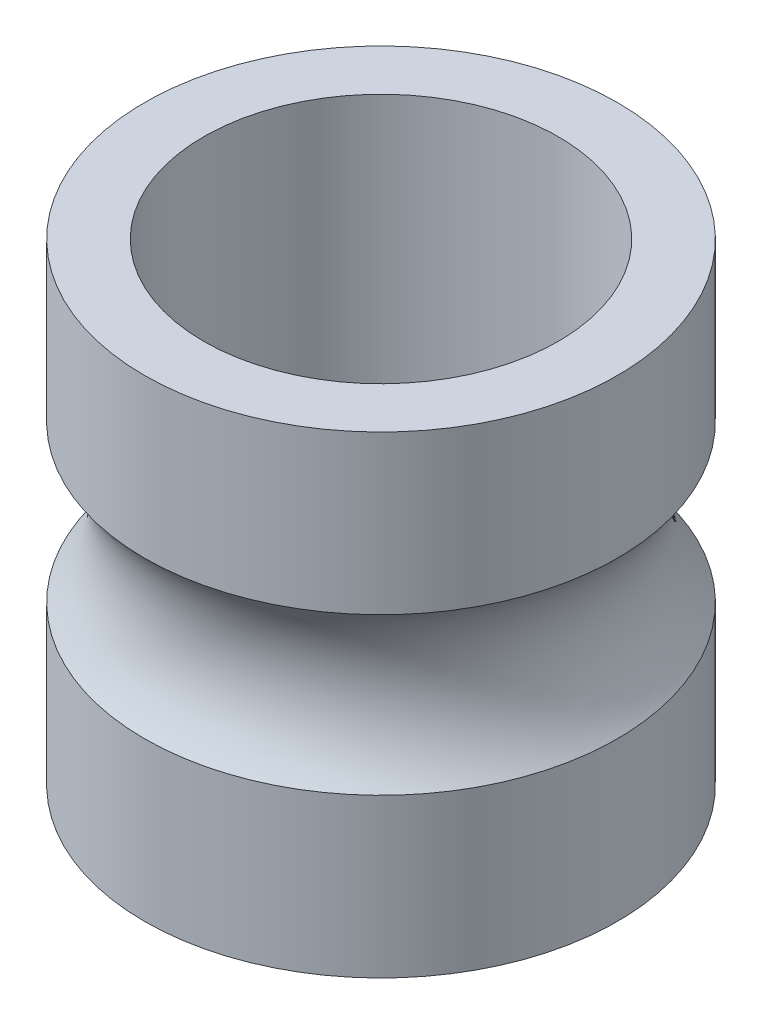
SolidWorks part; units mm, degrees
material "Chrome Stainless Steel"
ref_plane "Front Plane" through (0, 0, 0) normal (0, 0, 1) x (1, 0, 0)
ref_plane "Top Plane" through (0, 0, 0) normal (0, 1, 0) x (1, 0, 0)
ref_plane "Right Plane" through (0, 0, 0) normal (1, 0, 0) x (0, 0, -1)
sketch "Diameter Profile Sketch" plane through (0, 0, 0) normal (0, 1, 0) x (1, 0, 0)
  circle A0 centre (0, 0) radius 1.5
  circle A1 centre (0, 0) radius 2
  dimension "InnerDia" = 3
  dimension "Thickness" = 0.5
extrude "Diameter Profile" add sketch "Diameter Profile Sketch" along normal mid plane 4
sketch "Bearing Path Profile Sketch" plane through (0, 0, 0) normal (0, 0, 1) x (1, 0, 0)
  line L0 (0, 0) -> (2.75, 0) construction
  line L3 (0, 2) -> (0, -2) construction
  circle A0 centre (2.75, 0) radius 1
  dimension "BallDia" = 2
  dimension "YDim" = 0.75
  dimension "RefRadius" = 2.75
revolve "Bearing Path Profile" cut sketch "Bearing Path Profile Sketch" angle 360 about axis through (0, 2, 0) along (0, -1, 0)
